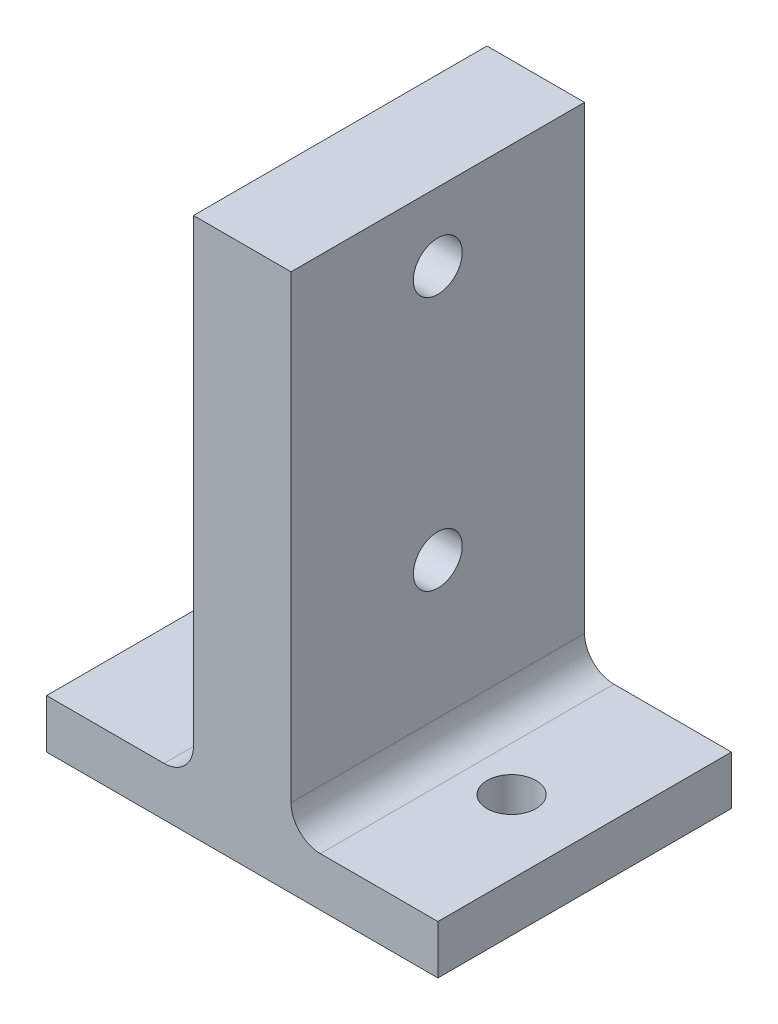
SolidWorks part; units mm, degrees
ref_plane "前视基准面" through (0, 0, 0) normal (0, 0, 1) x (1, 0, 0)
ref_plane "上视基准面" through (0, 0, 0) normal (0, 1, 0) x (1, 0, 0)
ref_plane "右视基准面" through (0, 0, 0) normal (1, 0, 0) x (0, 0, -1)
other "Configuration Table"
sketch "Sketch1" plane through (0, 0, 0) normal (0, 1, 0) x (1, 0, 0)
  line L1 (-20, 15) -> (20, 15)
  line L2 (-20, 15) -> (-20, -15)
  line L3 (-20, -15) -> (20, -15)
  line L4 (20, 15) -> (20, -15)
  line L5 (-20, 15) -> (20, -15) construction
  line L6 (-20, -15) -> (20, 15) construction
  point P0 (0, 0)
extrude "Boss-Extrude1" add sketch "Sketch1" along normal blind 5
sketch "Sketch2" plane through (0, 5, 0) normal (0, 1, 0) x (1, 0, 0)
  line L0 (-20, -15) -> (20, -15) construction
  line L1 (-4.9862, 15) -> (4.9862, 15)
  line L2 (-4.9862, 15) -> (-4.9862, -15)
  line L3 (-4.9862, -15) -> (4.9862, -15)
  line L4 (4.9862, 15) -> (4.9862, -15)
  line L5 (-4.9862, 15) -> (4.9862, -15) construction
  line L6 (-4.9862, -15) -> (4.9862, 15) construction
  point P0 (0, 0)
extrude "Boss-Extrude2" add sketch "Sketch2" along normal blind 50
sketch "Sketch3" plane through (0, 5, 0) normal (0, 1, 0) x (1, 0, 0)
  circle A0 centre (-12.5258, 0) radius 2.5
  circle A1 centre (12.5258, 0) radius 2.5
extrude "Cut-Extrude1" cut sketch "Sketch3" against normal through all
sketch "Sketch5" plane through (-4.9862, 0, 0) normal (-1, 0, 0) x (0, 0, 1)
  line L1 (-10, 48) -> (10, 48) construction
  line L2 (-10, 48) -> (-10, 22) construction
  line L3 (-10, 22) -> (10, 22) construction
  line L4 (10, 48) -> (10, 22) construction
  line L5 (-10, 48) -> (10, 22) construction
  line L6 (-10, 22) -> (10, 48) construction
  circle A0 centre (0, 48) radius 2.5
  circle A1 centre (0, 22) radius 2.5
  point P0 (0, 35)
extrude "Cut-Extrude2" cut sketch "Sketch5" against normal up to next
fillet "Fillet1" radius 3 2 edges at (4.9862, 5, 0) (-4.9862, 5, 0)
